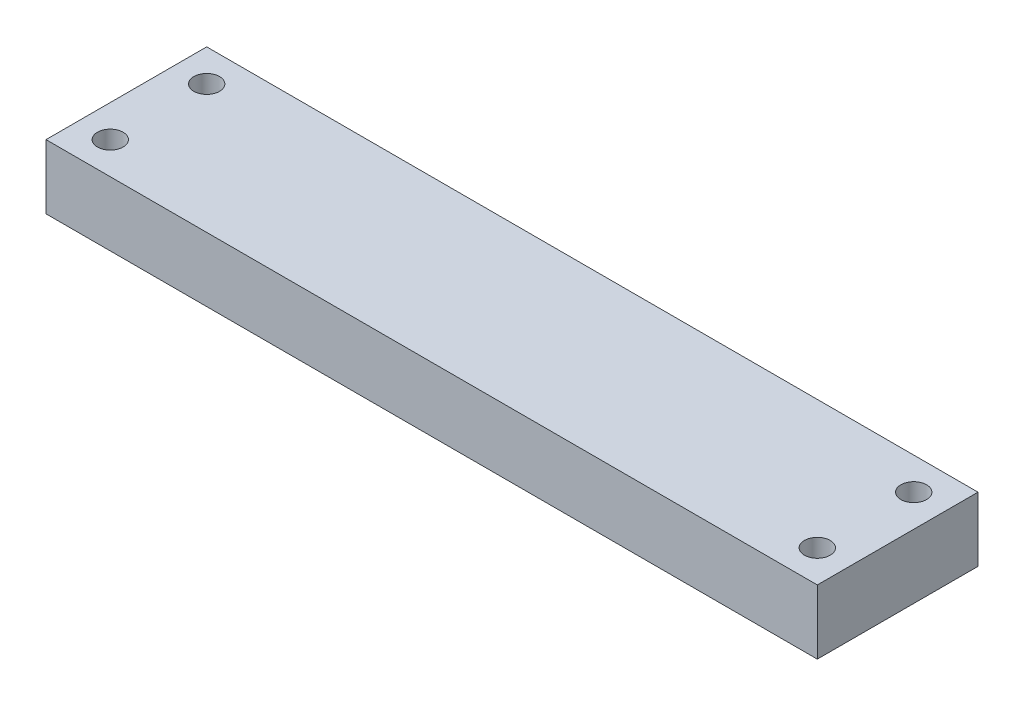
SolidWorks part; units mm, degrees
ref_plane "Front Plane" through (0, 0, 0) normal (0, 0, 1) x (1, 0, 0)
ref_plane "Top Plane" through (0, 0, 0) normal (0, 1, 0) x (1, 0, 0)
ref_plane "Right Plane" through (0, 0, 0) normal (1, 0, 0) x (0, 0, -1)
sketch "Sketch1" plane through (0, 0, 0) normal (0, 1, 0) x (1, 0, 0)
  line L1 (0, 0) -> (240, 0)
  line L2 (0, 0) -> (0, 50)
  line L3 (0, 50) -> (240, 50)
  line L4 (240, 0) -> (240, 50)
  circle A0 centre (10, 40) radius 4
  circle A1 centre (10, 10) radius 4
  circle A2 centre (230, 10) radius 4
  circle A3 centre (230, 40) radius 4
  dimension "D7" = 8
  dimension "D1" = 50
  dimension "D2" = 240
  dimension "D3" = 10
  dimension "D4" = 10
  dimension "D5" = 10
  dimension "D6" = 10
extrude "Boss-Extrude1" add sketch "Sketch1" along normal blind 20
